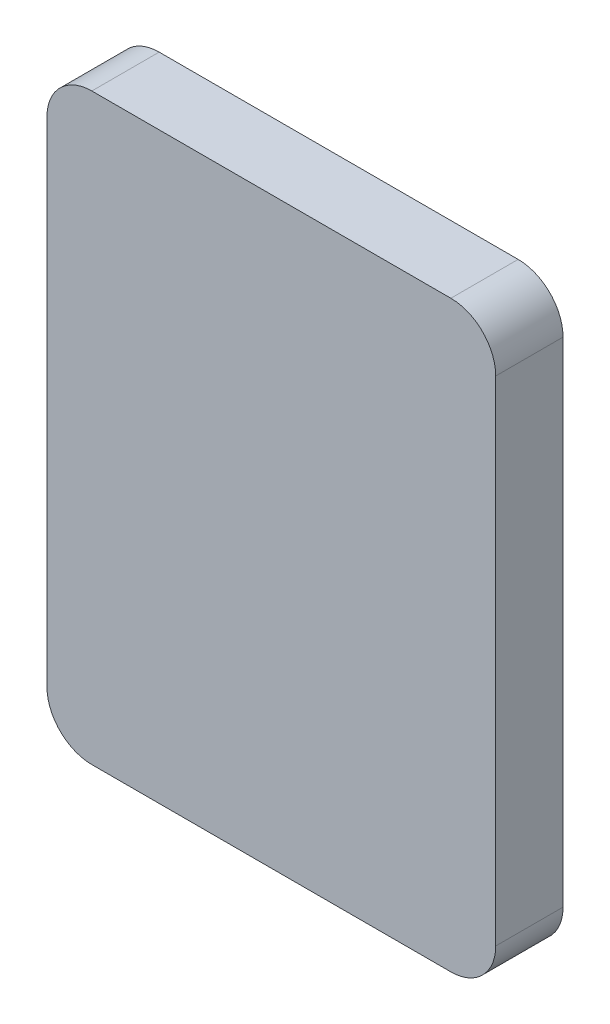
SolidWorks part; units mm, degrees
ref_plane "Plane1" through (0, 0, 0) normal (0, 0, 1) x (1, 0, 0)
ref_plane "Plane2" through (0, 0, 0) normal (0, 1, 0) x (1, 0, 0)
ref_plane "Plane3" through (0, 0, 0) normal (1, 0, 0) x (0, 0, -1)
sketch "Sketch1" plane through (0, 0, 0) normal (0, 0, 1) x (1, 0, 0)
  line L1 (4, -6.5) -> (-4, -6.5)
  line L2 (5, -5.5) -> (5, 5.5)
  line L3 (4, 6.5) -> (-4, 6.5)
  line L4 (-5, -5.5) -> (-5, 5.5)
  line L5 (5, -6.5) -> (-5, 6.5) construction
  line L6 (5, 6.5) -> (-5, -6.5) construction
  arc A0 (-4, -6.5) -> (-5, -5.5) centre (-4, -5.5) cw
  arc A1 (4, -6.5) -> (5, -5.5) centre (4, -5.5) ccw
  arc A2 (5, 5.5) -> (4, 6.5) centre (4, 5.5) ccw
  arc A3 (-4, 6.5) -> (-5, 5.5) centre (-4, 5.5) ccw
  point P0 (0, 0)
  dimension "D3" = 1
  dimension "D1" = 10
  dimension "D2" = 13
extrude "Boss-Extrude1" add sketch "Sketch1" along normal blind 1.5
